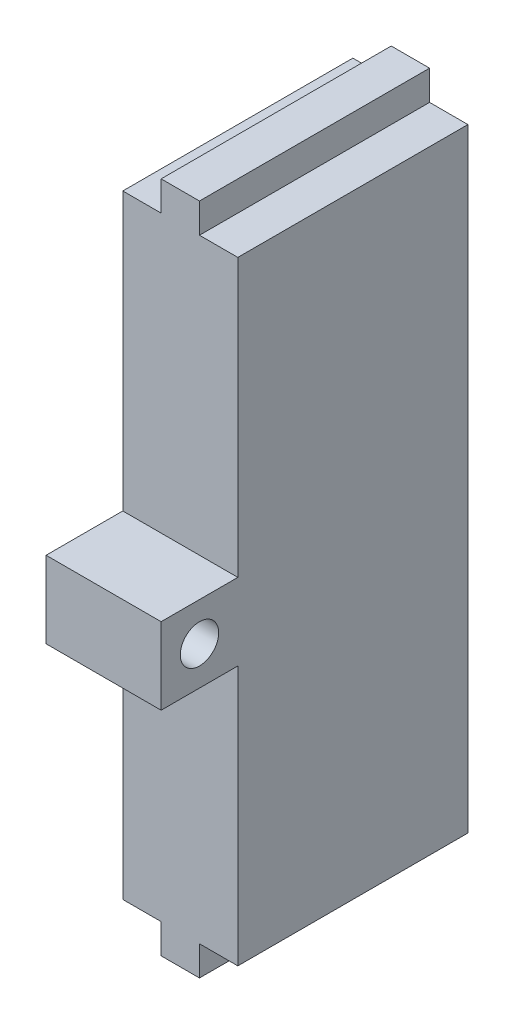
SolidWorks part; units mm, degrees
ref_plane "Front Plane" through (0, 0, 0) normal (0, 0, 1) x (1, 0, 0)
ref_plane "Top Plane" through (0, 0, 0) normal (0, 1, 0) x (1, 0, 0)
ref_plane "Right Plane" through (0, 0, 0) normal (1, 0, 0) x (0, 0, -1)
sketch "Sketch1" plane through (0, 0, 0) normal (0, 0, 1) x (1, 0, 0)
  line L0 (25, 0) -> (25, 19.3367)
  line L1 (25, 19.3367) -> (50, 19.3367)
  line L2 (0, 0) -> (25, 0)
  line L3 (0, 0) -> (0, -400)
  line L4 (0, -400) -> (25, -400)
  line L5 (75, 0) -> (75, -400)
  line L6 (50, 19.3367) -> (50, 0)
  line L7 (75, -200) -> (0, -200) construction
  line L8 (50, 0) -> (75, 0)
  line L9 (50, -419.3367) -> (50, -400)
  line L10 (25, -419.3367) -> (50, -419.3367)
  line L11 (25, -400) -> (25, -419.3367)
  line L12 (50, -400) -> (75, -400)
  dimension "D1" = 75
  dimension "D2" = 400
  dimension "D3" = 25
  dimension "D4" = 25
extrude "Boss-Extrude1" add sketch "Sketch1" along normal blind 150
sketch "Sketch2" plane through (0, 0, 150) normal (0, 0, 1) x (1, 0, 0)
  line L0 (0, 0) -> (0, -400) construction
  line L1 (0, -180.6633) -> (75, -180.6633)
  line L2 (0, -180.6633) -> (0, -230.6633)
  line L3 (0, -230.6633) -> (75, -230.6633)
  line L4 (75, -180.6633) -> (75, -230.6633)
  line L5 (75, -400) -> (75, 0) construction
  line L6 (50, 19.3367) -> (25, 19.3367) construction
  point P10 (0, -205.6633)
  dimension "D1" = 225
  dimension "D2" = 50
extrude "Boss-Extrude2" add sketch "Sketch2" along normal blind 50
sketch "Sketch3" plane through (0, 0, 0) normal (-1, 0, 0) x (0, 0, 1)
  line L0 (200, -180.6633) -> (200, -230.6633) construction
  line L1 (200, -180.6633) -> (150, -180.6633) construction
  circle A0 centre (175, -205.6633) radius 12.5
  dimension "D1" = 25
  dimension "D2" = 25
  dimension "D3" = 25
extrude "Cut-Extrude1" cut sketch "Sketch3" against normal blind 167
